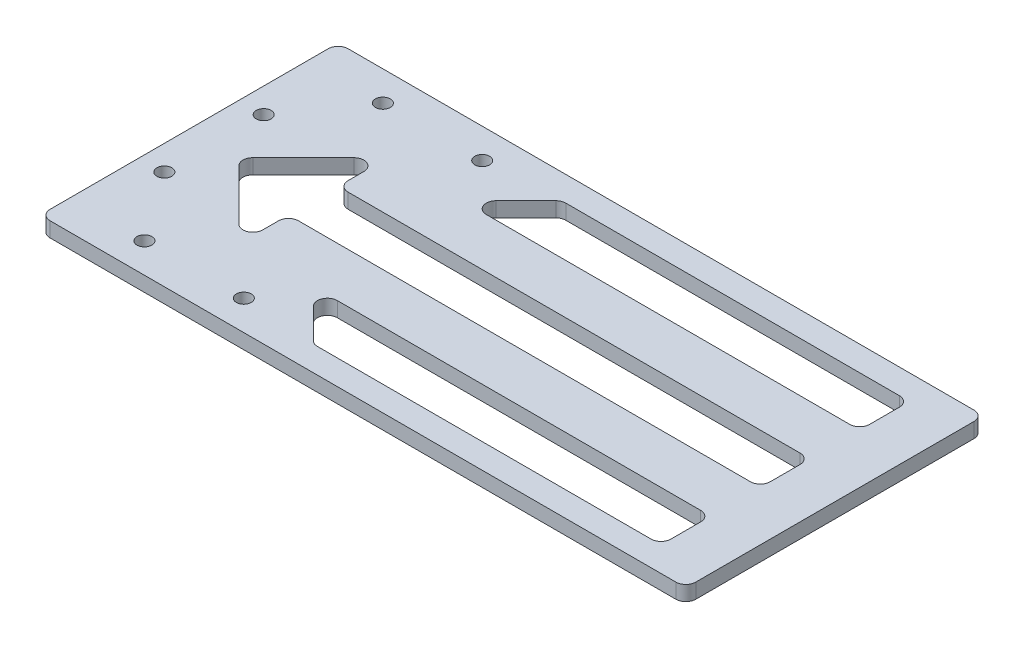
SolidWorks part; units mm, degrees
ref_plane "前视基准面" through (0, 0, 0) normal (0, 0, 1) x (1, 0, 0)
ref_plane "上视基准面" through (0, 0, 0) normal (0, 1, 0) x (1, 0, 0)
ref_plane "右视基准面" through (0, 0, 0) normal (1, 0, 0) x (0, 0, -1)
other "Configuration Table"
sketch "草图1" plane through (0, 0, 0) normal (0, 1, 0) x (1, 0, 0)
  line L0 (-60, 10) -> (-60, -10) construction
  line L1 (-65, 30) -> (65, 30)
  line L2 (-65, 30) -> (-65, -30)
  line L3 (-65, -30) -> (65, -30)
  line L4 (65, 30) -> (65, -30)
  line L5 (-65, 30) -> (65, -30) construction
  line L6 (-65, -30) -> (65, 30) construction
  line L7 (-60, 0) -> (0, 0) construction
  circle A0 centre (-60, 10) radius 1.5
  circle A1 centre (-60, -10) radius 1.5
  point P0 (0, 0)
  dimension "D3" = 3
  dimension "D1" = 60
  dimension "D2" = 130
  dimension "D4" = 20
  dimension "D5" = 5
extrude "凸台-拉伸1" add sketch "草图1" along normal blind 3
sketch "草图2" plane through (0, 3, 0) normal (0, 1, 0) x (1, 0, 0)
  line L0 (-30, 24) -> (-50, 24) construction
  line L1 (65, 30) -> (-65, 30) construction
  line L2 (-65, 30) -> (-65, -30) construction
  line L3 (-65, 0) -> (0, 0) construction
  line L4 (-30, -24) -> (-50, -24) construction
  circle A0 centre (-30, 24) radius 1.5
  circle A1 centre (-50, 24) radius 1.5
  circle A2 centre (-50, -24) radius 1.5
  circle A3 centre (-30, -24) radius 1.5
  dimension "D2" = 3
  dimension "D1" = 6
  dimension "D3" = 15
  dimension "D4" = 20
extrude "切除-拉伸1" cut sketch "草图2" against normal through all
sketch "草图3" plane through (0, 3, 0) normal (0, 1, 0) x (1, 0, 0)
  line L0 (0, 0) -> (-55, 0) construction
  line L1 (-55, 0) -> (-40, 15)
  line L2 (-40, 15) -> (-40, 5)
  line L3 (-40, 5) -> (55, 5)
  line L4 (55, 5) -> (55, -5)
  line L5 (55, 0) -> (0, 0) construction
  line L6 (-65, 30) -> (-65, -30) construction
  line L7 (65, -30) -> (65, 30) construction
  line L8 (-40, -5) -> (55, -5)
  line L9 (-40, -15) -> (-40, -5)
  line L10 (-55, 0) -> (-40, -15)
  line L11 (-15, 25) -> (55, 25)
  line L12 (55, 25) -> (55, 15)
  line L13 (55, 15) -> (-25, 15)
  line L14 (-25, 15) -> (-15, 25)
  line L15 (65, 30) -> (-65, 30) construction
  line L16 (55, -15) -> (-25, -15)
  line L17 (55, -25) -> (55, -15)
  line L18 (-15, -25) -> (55, -25)
  line L19 (-25, -15) -> (-15, -25)
  point P20 (-27.4794, 10)
  point P21 (-27.0162, 15)
  dimension "D1" = 5
  dimension "D2" = 10
  dimension "D3" = 10
  dimension "D4" = 15
  dimension "D5" = 10
  dimension "D6" = 5
  dimension "D7" = 10
  dimension "D8" = 10
  dimension "D9" = 10
  dimension "D10" = 80
extrude "切除-拉伸2" cut sketch "草图3" against normal through all
fillet "圆角1" radius 2 19 edges at (-65, 1.5, 30) (-65, 1.5, -30) (65, 1.5, -30) (-40, 1.5, 15) (-40, 1.5, 5) (55, 1.5, 5) (55, 1.5, -5) (-40, 1.5, -5) (-40, 1.5, -15) (-55, 1.5, 0) (-25, 1.5, -15) (55, 1.5, -15) (55, 1.5, -25) (-15, 1.5, -25) (55, 1.5, 15) (-25, 1.5, 15) (-15, 1.5, 25) (55, 1.5, 25) (65, 1.5, 30)
